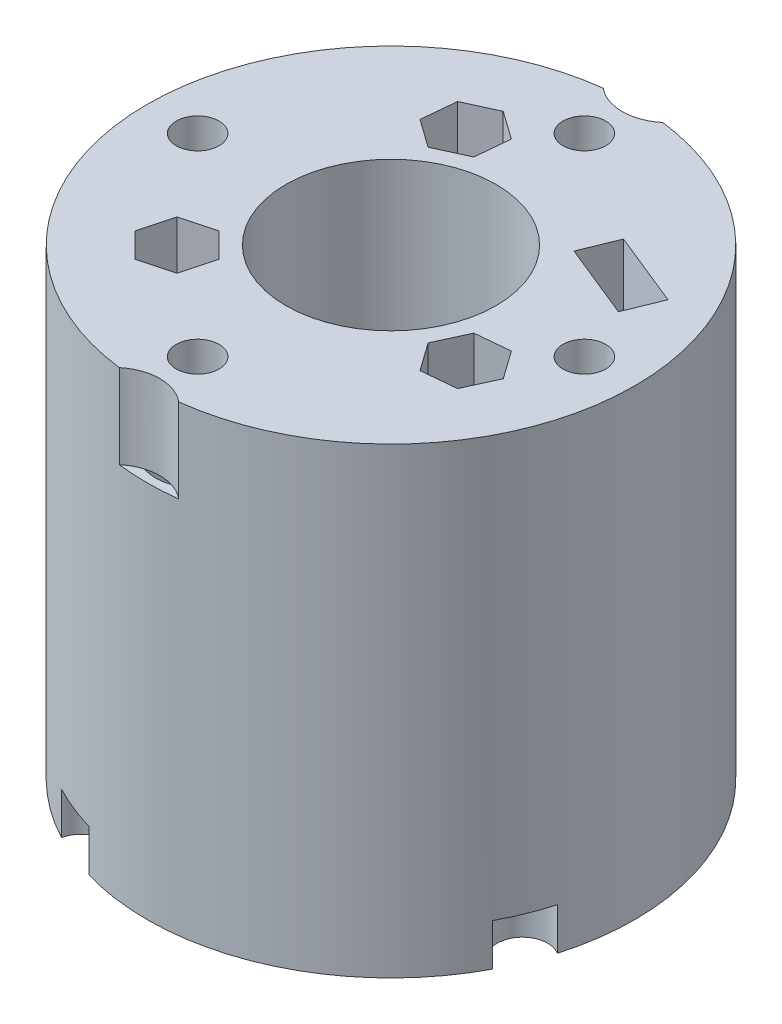
SolidWorks part; units mm, degrees
material "ABS"
ref_plane "Front Plane" through (0, 0, 0) normal (0, 0, 1) x (1, 0, 0)
ref_plane "Top Plane" through (0, 0, 0) normal (0, 1, 0) x (1, 0, 0)
ref_plane "Right Plane" through (0, 0, 0) normal (1, 0, 0) x (0, 0, -1)
sketch "Sketch1" plane through (0, 0, 0) normal (0, 1, 0) x (1, 0, 0)
  circle A0 centre (0, 0) radius 29
  dimension "D1" = 58
extrude "Boss-Extrude1" add sketch "Sketch1" along normal blind 55
sketch "Sketch5" plane through (0, 0, 0) normal (0, -1, 0) x (1, 0, 0)
  circle A0 centre (-23, 0) radius 5
  dimension "D1" = 10
  dimension "D2" = 23
extrude "Cut-Extrude2" cut sketch "Sketch5" against normal blind 45
sketch "Sketch4" plane through (0, 0, 0) normal (0, -1, 0) x (1, 0, 0)
  circle A0 centre (-23, 0) radius 2.55
  circle A1 centre (-23, 0) radius 5 construction
  dimension "D3" = 5.1
extrude "Cut-Extrude1" cut sketch "Sketch4" against normal through all
pattern_circular "CirPattern2" count 4 over 360 about axis through (0, 0, 0) along (0, 1, 0) of "Cut-Extrude2", "Cut-Extrude1"
sketch "Sketch6" plane through (0, 0, 0) normal (0, -1, 0) x (1, 0, 0)
  circle A0 centre (0, 0) radius 12.5
  dimension "D1" = 25
extrude "Cut-Extrude3" cut sketch "Sketch6" against normal through all
sketch "Sketch8" plane through (0, 0, 0) normal (0, -1, 0) x (1, 0, 0)
  circle A0 centre (-10.6014, 26.2393) radius 3
  circle A1 centre (-26.2393, -10.6014) radius 3
  circle A2 centre (10.6014, -26.2393) radius 3
  circle A3 centre (26.2393, 10.6014) radius 3
  dimension "D1" = 6
extrude "Cut-Extrude4" cut sketch "Sketch8" against normal blind 5
sketch "Sketch9" plane through (0, 0, 0) normal (0, -1, 0) x (1, 0, 0)
  line L0 (20.6109, -6.1585) -> (22.5973, -11.0507)
  line L1 (22.5973, -11.0507) -> (12.9983, -14.9481)
  line L2 (11.012, -10.056) -> (12.9983, -14.9481)
  line L3 (20.6109, -6.1585) -> (11.012, -10.056)
  line L4 (20.5559, -6.2888) -> (22.467, -10.9956) construction
  line L5 (22.467, -10.9956) -> (13.0534, -14.8178) construction
  line L6 (11.1422, -10.111) -> (13.0534, -14.8178) construction
  line L7 (20.5559, -6.2888) -> (11.1422, -10.111) construction
  line L10 (19.8304, -12.0661) -> (18.0433, -12.7918) construction
  line L11 (20.7064, -6.6595) -> (22.3165, -10.625) construction
  dimension "D1" = 5.08
  dimension "D2" = 10.16
  dimension "D3" = 0.1
extrude "Cut-Extrude5" cut sketch "Sketch9" against normal blind 1
sketch "Sketch11" plane through (0, 1, 0) normal (0, -1, 0) x (1, 0, 0)
  line L0 (22.103, -10.8419) -> (20.4021, -6.6528)
  line L2 (22.103, -10.8419) -> (13.2071, -14.4539)
  line L5 (20.4021, -6.6528) -> (11.5062, -10.2648)
  line L6 (13.2071, -14.4539) -> (11.5062, -10.2648)
  circle A0 centre (20.8125, -10.2967) radius 0.9906 construction
  circle A1 centre (19.8569, -7.9433) radius 0.9906 construction
  circle A2 centre (12.7967, -10.81) radius 0.9906 construction
  circle A3 centre (15.1501, -9.8544) radius 0.9906 construction
  circle A4 centre (18.4591, -11.2523) radius 0.9906 construction
extrude "Cut-Extrude6" cut sketch "Sketch11" against normal through all
sketch "Sketch12" plane through (0, 0, 0) normal (0, -1, 0) x (1, 0, 0)
  circle A0 centre (7.1175, -17.6165) radius 3.9
extrude "Cut-Extrude7" cut sketch "Sketch12" against normal blind 6
sketch "Sketch13" plane through (0, 55, 0) normal (0, 1, 0) x (1, 0, 0)
  line L0 (16.3696, -7.4858) -> (13.1411, -6.0094) construction
  line L1 (18.7456, -10.8261) -> (20.4504, -7.0982)
  line L2 (20.4504, -7.0982) -> (18.0743, -3.7579)
  line L3 (18.0743, -3.7579) -> (13.9935, -4.1455)
  line L4 (13.9935, -4.1455) -> (12.2887, -7.8734)
  line L5 (12.2887, -7.8734) -> (14.6648, -11.2137)
  line L6 (14.6648, -11.2137) -> (18.7456, -10.8261)
  line L7 (-7.4858, 16.3696) -> (-6.0094, 13.1411) construction
  line L8 (-4.1455, 13.9935) -> (-3.7579, 18.0743)
  line L9 (-3.7579, 18.0743) -> (-7.0982, 20.4504)
  line L10 (-7.0982, 20.4504) -> (-10.8261, 18.7456)
  line L11 (-10.8261, 18.7456) -> (-11.2137, 14.6648)
  line L12 (-11.2137, 14.6648) -> (-7.8734, 12.2887)
  line L13 (-7.8734, 12.2887) -> (-4.1455, 13.9935)
  line L14 (-12.7279, -12.7279) -> (-10.2177, -10.2177) construction
  line L15 (-13.7889, -16.6874) -> (-9.8294, -15.6265)
  line L16 (-9.8294, -15.6265) -> (-8.7684, -11.667)
  line L17 (-8.7684, -11.667) -> (-11.667, -8.7684)
  line L18 (-11.667, -8.7684) -> (-15.6265, -9.8294)
  line L19 (-15.6265, -9.8294) -> (-16.6874, -13.7889)
  line L20 (-16.6874, -13.7889) -> (-13.7889, -16.6874)
  line L21 (-7.4858, 16.3696) -> (16.3696, -7.4858) construction
  line L22 (16.3696, -7.4858) -> (-12.7279, -12.7279) construction
  line L23 (-12.7279, -12.7279) -> (-7.4858, 16.3696) construction
  circle A0 centre (16.3696, -7.4858) radius 3.55 construction
  circle A1 centre (23, 0) radius 2.55 construction
  circle A2 centre (-7.4858, 16.3696) radius 3.55 construction
  circle A3 centre (0, 23) radius 2.55 construction
  circle A4 centre (-12.7279, -12.7279) radius 3.55 construction
  point P1 (-6.0094, 13.1411)
  dimension "D1" = 7.1
  dimension "D2" = 18
  dimension "D3" = 10
  dimension "D4" = 7.1
  dimension "D5" = 18
  dimension "D6" = 10
  dimension "D7" = 7.1
  dimension "D8" = 18
extrude "Cut-Extrude8" cut sketch "Sketch13" against normal blind 45
sketch "Sketch14" plane through (0, 55, 0) normal (0, 1, 0) x (1, 0, 0)
  circle A0 centre (-7.4858, 16.3696) radius 2.15
  circle A1 centre (16.3696, -7.4858) radius 2.15
  circle A2 centre (-12.7279, -12.7279) radius 2.15
  dimension "D1" = 4.3
extrude "Cut-Extrude9" cut sketch "Sketch14" against normal through all
sketch "Sketch16" plane through (0, 55, 0) normal (0, 1, 0) x (1, 0, 0)
  circle A0 centre (0, 33) radius 5.5
  circle A1 centre (0, -33) radius 5.5
  dimension "D1" = 11
extrude "Cut-Extrude10" cut sketch "Sketch16" against normal blind 10
